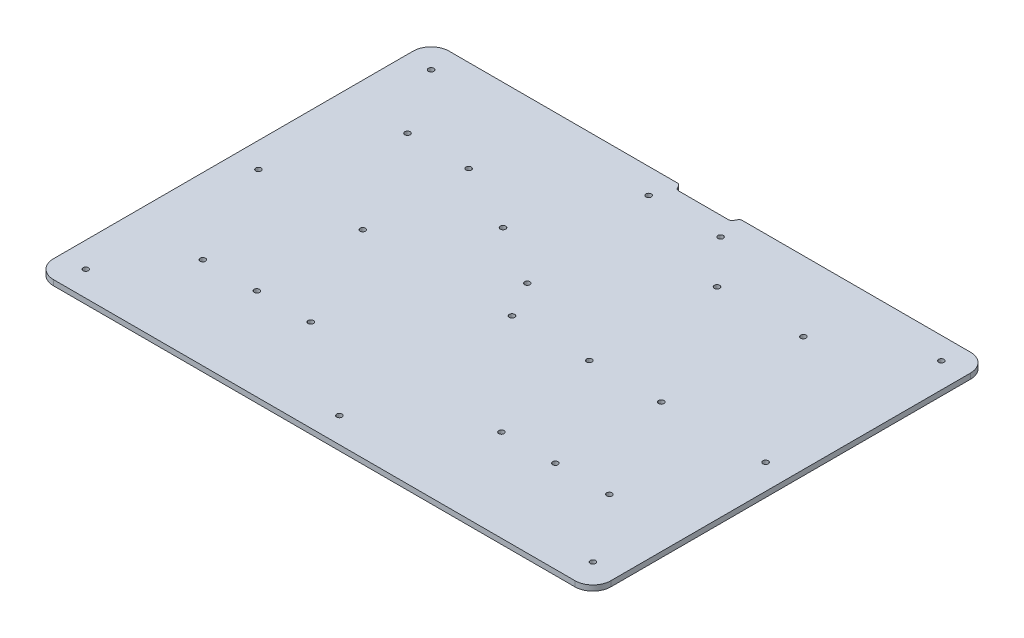
SolidWorks part; units mm, degrees
ref_plane "前视基准面" through (0, 0, 0) normal (0, 0, 1) x (1, 0, 0)
ref_plane "上视基准面" through (0, 0, 0) normal (0, 1, 0) x (1, 0, 0)
ref_plane "右视基准面" through (0, 0, 0) normal (1, 0, 0) x (0, 0, -1)
sketch "草图1" plane through (0, 0, 0) normal (0, 1, 0) x (1, 0, 0)
  line L0 (183.25, -128.5) -> (183.25, -131.5) construction
  line L1 (10, 0) -> (136.8844, 0)
  line L2 (0, -10) -> (0, -210)
  line L3 (10, -220) -> (300, -220)
  line L4 (310, -10) -> (310, -210)
  line L5 (28.75, -14.75) -> (47.25, -14.75) construction
  line L6 (28.75, -14.75) -> (28.75, -33.25) construction
  line L7 (28.75, -33.25) -> (47.25, -33.25) construction
  line L8 (173, -85) -> (173, 0) construction
  line L9 (173, -85) -> (310, -85) construction
  line L10 (190, -66) -> (190, 0) construction
  line L11 (215, -58) -> (215, 0) construction
  line L12 (241, -58) -> (241, 0) construction
  line L13 (247, -84) -> (247, 0) construction
  line L14 (222, -84) -> (222, 0) construction
  line L15 (0, -220) -> (310, 0) construction
  line L16 (241, -58) -> (310, -58) construction
  line L17 (247, -84) -> (310, -84) construction
  line L18 (215, -58) -> (310, -58) construction
  line L19 (222, -84) -> (310, -84) construction
  line L20 (190, -66) -> (310, -66) construction
  line L21 (310, -220) -> (0, 0) construction
  line L22 (141.1791, -3.5) -> (143.5, -3.5)
  line L23 (139.4291, -2.4682) -> (138.6344, -1.0318)
  line L24 (170.5709, -2.4682) -> (171.3656, -1.0318)
  line L25 (173.1156, 0) -> (300, 0)
  line L26 (155, -110) -> (155, -220) construction
  line L27 (47.25, -14.75) -> (47.25, -33.25) construction
  line L28 (28.75, -14.75) -> (47.25, -33.25) construction
  line L29 (28.75, -33.25) -> (47.25, -14.75) construction
  line L30 (52.75, -14.75) -> (71.25, -14.75) construction
  line L31 (52.75, -14.75) -> (52.75, -33.25) construction
  line L32 (52.75, -33.25) -> (71.25, -33.25) construction
  line L33 (71.25, -14.75) -> (71.25, -33.25) construction
  line L34 (52.75, -14.75) -> (71.25, -33.25) construction
  line L35 (52.75, -33.25) -> (71.25, -14.75) construction
  line L36 (76.75, -14.75) -> (95.25, -14.75) construction
  line L37 (76.75, -14.75) -> (76.75, -33.25) construction
  line L38 (76.75, -33.25) -> (95.25, -33.25) construction
  line L39 (95.25, -14.75) -> (95.25, -33.25) construction
  line L40 (76.75, -14.75) -> (95.25, -33.25) construction
  line L41 (76.75, -33.25) -> (95.25, -14.75) construction
  line L42 (100.75, -14.75) -> (119.25, -14.75) construction
  line L43 (100.75, -14.75) -> (100.75, -33.25) construction
  line L44 (100.75, -33.25) -> (119.25, -33.25) construction
  line L45 (119.25, -14.75) -> (119.25, -33.25) construction
  line L46 (100.75, -14.75) -> (119.25, -33.25) construction
  line L47 (100.75, -33.25) -> (119.25, -14.75) construction
  line L48 (188.75, -14.75) -> (207.25, -14.75) construction
  line L49 (188.75, -14.75) -> (188.75, -33.25) construction
  line L50 (188.75, -33.25) -> (207.25, -33.25) construction
  line L51 (207.25, -14.75) -> (207.25, -33.25) construction
  line L52 (188.75, -14.75) -> (207.25, -33.25) construction
  line L53 (188.75, -33.25) -> (207.25, -14.75) construction
  line L54 (212.75, -14.75) -> (231.25, -14.75) construction
  line L55 (212.75, -14.75) -> (212.75, -33.25) construction
  line L56 (212.75, -33.25) -> (231.25, -33.25) construction
  line L57 (231.25, -14.75) -> (231.25, -33.25) construction
  line L58 (212.75, -14.75) -> (231.25, -33.25) construction
  line L59 (212.75, -33.25) -> (231.25, -14.75) construction
  line L60 (236.75, -14.75) -> (255.25, -14.75) construction
  line L61 (236.75, -14.75) -> (236.75, -33.25) construction
  line L62 (236.75, -33.25) -> (255.25, -33.25) construction
  line L63 (255.25, -14.75) -> (255.25, -33.25) construction
  line L64 (236.75, -14.75) -> (255.25, -33.25) construction
  line L65 (236.75, -33.25) -> (255.25, -14.75) construction
  line L66 (260.75, -14.75) -> (279.25, -14.75) construction
  line L67 (260.75, -14.75) -> (260.75, -33.25) construction
  line L68 (260.75, -33.25) -> (279.25, -33.25) construction
  line L69 (279.25, -14.75) -> (279.25, -33.25) construction
  line L70 (260.75, -14.75) -> (279.25, -33.25) construction
  line L71 (260.75, -33.25) -> (279.25, -14.75) construction
  line L72 (183, -123) -> (197, -123) construction
  line L73 (183, -123) -> (183, -128.25) construction
  line L74 (183, -137) -> (197, -137) construction
  line L75 (197, -123) -> (197, -128.25) construction
  line L76 (183, -123) -> (197, -137) construction
  line L77 (183, -137) -> (197, -123) construction
  line L78 (183.25, -128.5) -> (183, -128.25) construction
  line L79 (183.25, -131.5) -> (183, -131.75) construction
  line L80 (196.75, -128.5) -> (196.75, -131.5) construction
  line L81 (196.75, -128.5) -> (197, -128.25) construction
  line L82 (196.75, -131.5) -> (197, -131.75) construction
  line L83 (183, -131.75) -> (183, -137) construction
  line L84 (197, -131.75) -> (197, -137) construction
  line L85 (31.25, -22.5) -> (31.25, -25.5) construction
  line L86 (31, -17) -> (45, -17) construction
  line L87 (31, -17) -> (31, -22.25) construction
  line L88 (31, -31) -> (45, -31) construction
  line L89 (45, -17) -> (45, -22.25) construction
  line L90 (31, -17) -> (45, -31) construction
  line L91 (31, -31) -> (45, -17) construction
  line L92 (31.25, -22.5) -> (31, -22.25) construction
  line L93 (31.25, -25.5) -> (31, -25.75) construction
  line L94 (44.75, -22.5) -> (44.75, -25.5) construction
  line L95 (44.75, -22.5) -> (45, -22.25) construction
  line L96 (44.75, -25.5) -> (45, -25.75) construction
  line L97 (31, -25.75) -> (31, -31) construction
  line L98 (45, -25.75) -> (45, -31) construction
  line L99 (55.25, -22.5) -> (55.25, -25.5) construction
  line L100 (55, -17) -> (69, -17) construction
  line L101 (55, -17) -> (55, -22.25) construction
  line L102 (55, -31) -> (69, -31) construction
  line L103 (69, -17) -> (69, -22.25) construction
  line L104 (55, -17) -> (69, -31) construction
  line L105 (55, -31) -> (69, -17) construction
  line L106 (55.25, -22.5) -> (55, -22.25) construction
  line L107 (55.25, -25.5) -> (55, -25.75) construction
  line L108 (68.75, -22.5) -> (68.75, -25.5) construction
  line L109 (68.75, -22.5) -> (69, -22.25) construction
  line L110 (68.75, -25.5) -> (69, -25.75) construction
  line L111 (55, -25.75) -> (55, -31) construction
  line L112 (69, -25.75) -> (69, -31) construction
  line L113 (79.25, -22.5) -> (79.25, -25.5) construction
  line L114 (79, -17) -> (93, -17) construction
  line L115 (79, -17) -> (79, -22.25) construction
  line L116 (79, -31) -> (93, -31) construction
  line L117 (93, -17) -> (93, -22.25) construction
  line L118 (79, -17) -> (93, -31) construction
  line L119 (79, -31) -> (93, -17) construction
  line L120 (79.25, -22.5) -> (79, -22.25) construction
  line L121 (79.25, -25.5) -> (79, -25.75) construction
  line L122 (92.75, -22.5) -> (92.75, -25.5) construction
  line L123 (92.75, -22.5) -> (93, -22.25) construction
  line L124 (92.75, -25.5) -> (93, -25.75) construction
  line L125 (79, -25.75) -> (79, -31) construction
  line L126 (93, -25.75) -> (93, -31) construction
  line L127 (103.25, -22.5) -> (103.25, -25.5) construction
  line L128 (103, -17) -> (117, -17) construction
  line L129 (103, -17) -> (103, -22.25) construction
  line L130 (103, -31) -> (117, -31) construction
  line L131 (117, -17) -> (117, -22.25) construction
  line L132 (103, -17) -> (117, -31) construction
  line L133 (103, -31) -> (117, -17) construction
  line L134 (103.25, -22.5) -> (103, -22.25) construction
  line L135 (103.25, -25.5) -> (103, -25.75) construction
  line L136 (116.75, -22.5) -> (116.75, -25.5) construction
  line L137 (116.75, -22.5) -> (117, -22.25) construction
  line L138 (116.75, -25.5) -> (117, -25.75) construction
  line L139 (103, -25.75) -> (103, -31) construction
  line L140 (117, -25.75) -> (117, -31) construction
  line L141 (191.25, -22.5) -> (191.25, -25.5) construction
  line L142 (191, -17) -> (205, -17) construction
  line L143 (191, -17) -> (191, -22.25) construction
  line L144 (191, -31) -> (205, -31) construction
  line L145 (205, -17) -> (205, -22.25) construction
  line L146 (191, -17) -> (205, -31) construction
  line L147 (191, -31) -> (205, -17) construction
  line L148 (191.25, -22.5) -> (191, -22.25) construction
  line L149 (191.25, -25.5) -> (191, -25.75) construction
  line L150 (204.75, -22.5) -> (204.75, -25.5) construction
  line L151 (204.75, -22.5) -> (205, -22.25) construction
  line L152 (204.75, -25.5) -> (205, -25.75) construction
  line L153 (191, -25.75) -> (191, -31) construction
  line L154 (205, -25.75) -> (205, -31) construction
  line L155 (215.25, -22.5) -> (215.25, -25.5) construction
  line L156 (215, -17) -> (229, -17) construction
  line L157 (215, -17) -> (215, -22.25) construction
  line L158 (215, -31) -> (229, -31) construction
  line L159 (229, -17) -> (229, -22.25) construction
  line L160 (215, -17) -> (229, -31) construction
  line L161 (215, -31) -> (229, -17) construction
  line L162 (215.25, -22.5) -> (215, -22.25) construction
  line L163 (215.25, -25.5) -> (215, -25.75) construction
  line L164 (228.75, -22.5) -> (228.75, -25.5) construction
  line L165 (228.75, -22.5) -> (229, -22.25) construction
  line L166 (228.75, -25.5) -> (229, -25.75) construction
  line L167 (215, -25.75) -> (215, -31) construction
  line L168 (229, -25.75) -> (229, -31) construction
  line L169 (239.25, -22.5) -> (239.25, -25.5) construction
  line L170 (239, -17) -> (253, -17) construction
  line L171 (239, -17) -> (239, -22.25) construction
  line L172 (239, -31) -> (253, -31) construction
  line L173 (253, -17) -> (253, -22.25) construction
  line L174 (239, -17) -> (253, -31) construction
  line L175 (239, -31) -> (253, -17) construction
  line L176 (239.25, -22.5) -> (239, -22.25) construction
  line L177 (239.25, -25.5) -> (239, -25.75) construction
  line L178 (252.75, -22.5) -> (252.75, -25.5) construction
  line L179 (252.75, -22.5) -> (253, -22.25) construction
  line L180 (252.75, -25.5) -> (253, -25.75) construction
  line L181 (239, -25.75) -> (239, -31) construction
  line L182 (253, -25.75) -> (253, -31) construction
  line L183 (263.25, -22.5) -> (263.25, -25.5) construction
  line L184 (263, -17) -> (277, -17) construction
  line L185 (263, -17) -> (263, -22.25) construction
  line L186 (263, -31) -> (277, -31) construction
  line L187 (277, -17) -> (277, -22.25) construction
  line L188 (263, -17) -> (277, -31) construction
  line L189 (263, -31) -> (277, -17) construction
  line L190 (263.25, -22.5) -> (263, -22.25) construction
  line L191 (263.25, -25.5) -> (263, -25.75) construction
  line L192 (276.75, -22.5) -> (276.75, -25.5) construction
  line L193 (276.75, -22.5) -> (277, -22.25) construction
  line L194 (276.75, -25.5) -> (277, -25.75) construction
  line L195 (263, -25.75) -> (263, -31) construction
  line L196 (277, -25.75) -> (277, -31) construction
  line L197 (259.25, -64.5) -> (259.25, -67.5) construction
  line L198 (259, -59) -> (273, -59) construction
  line L199 (259, -59) -> (259, -64.25) construction
  line L200 (259, -73) -> (273, -73) construction
  line L201 (273, -59) -> (273, -64.25) construction
  line L202 (259, -59) -> (273, -73) construction
  line L203 (259, -73) -> (273, -59) construction
  line L204 (259.25, -64.5) -> (259, -64.25) construction
  line L205 (259.25, -67.5) -> (259, -67.75) construction
  line L206 (272.75, -64.5) -> (272.75, -67.5) construction
  line L207 (272.75, -64.5) -> (273, -64.25) construction
  line L208 (272.75, -67.5) -> (273, -67.75) construction
  line L209 (259, -67.75) -> (259, -73) construction
  line L210 (273, -67.75) -> (273, -73) construction
  line L211 (240.25, -82.5) -> (240.25, -85.5) construction
  line L212 (240, -77) -> (254, -77) construction
  line L213 (240, -77) -> (240, -82.25) construction
  line L214 (240, -91) -> (254, -91) construction
  line L215 (254, -77) -> (254, -82.25) construction
  line L216 (240, -77) -> (254, -91) construction
  line L217 (240, -91) -> (254, -77) construction
  line L218 (240.25, -82.5) -> (240, -82.25) construction
  line L219 (240.25, -85.5) -> (240, -85.75) construction
  line L220 (253.75, -82.5) -> (253.75, -85.5) construction
  line L221 (253.75, -82.5) -> (254, -82.25) construction
  line L222 (253.75, -85.5) -> (254, -85.75) construction
  line L223 (240, -85.75) -> (240, -91) construction
  line L224 (254, -85.75) -> (254, -91) construction
  line L225 (234.25, -56.5) -> (234.25, -59.5) construction
  line L226 (234, -51) -> (248, -51) construction
  line L227 (234, -51) -> (234, -56.25) construction
  line L228 (234, -65) -> (248, -65) construction
  line L229 (248, -51) -> (248, -56.25) construction
  line L230 (234, -51) -> (248, -65) construction
  line L231 (234, -65) -> (248, -51) construction
  line L232 (234.25, -56.5) -> (234, -56.25) construction
  line L233 (234.25, -59.5) -> (234, -59.75) construction
  line L234 (247.75, -56.5) -> (247.75, -59.5) construction
  line L235 (247.75, -56.5) -> (248, -56.25) construction
  line L236 (247.75, -59.5) -> (248, -59.75) construction
  line L237 (234, -59.75) -> (234, -65) construction
  line L238 (248, -59.75) -> (248, -65) construction
  line L239 (215.25, -82.5) -> (215.25, -85.5) construction
  line L240 (215, -77) -> (229, -77) construction
  line L241 (215, -77) -> (215, -82.25) construction
  line L242 (215, -91) -> (229, -91) construction
  line L243 (229, -77) -> (229, -82.25) construction
  line L244 (215, -77) -> (229, -91) construction
  line L245 (215, -91) -> (229, -77) construction
  line L246 (215.25, -82.5) -> (215, -82.25) construction
  line L247 (215.25, -85.5) -> (215, -85.75) construction
  line L248 (228.75, -82.5) -> (228.75, -85.5) construction
  line L249 (228.75, -82.5) -> (229, -82.25) construction
  line L250 (228.75, -85.5) -> (229, -85.75) construction
  line L251 (215, -85.75) -> (215, -91) construction
  line L252 (229, -85.75) -> (229, -91) construction
  line L253 (29.25, -95.5) -> (29.25, -98.5) construction
  line L254 (29, -90) -> (43, -90) construction
  line L255 (29, -90) -> (29, -95.25) construction
  line L256 (29, -104) -> (43, -104) construction
  line L257 (43, -90) -> (43, -95.25) construction
  line L258 (29, -90) -> (43, -104) construction
  line L259 (29, -104) -> (43, -90) construction
  line L260 (29.25, -95.5) -> (29, -95.25) construction
  line L261 (29.25, -98.5) -> (29, -98.75) construction
  line L262 (42.75, -95.5) -> (42.75, -98.5) construction
  line L263 (42.75, -95.5) -> (43, -95.25) construction
  line L264 (42.75, -98.5) -> (43, -98.75) construction
  line L265 (29, -98.75) -> (29, -104) construction
  line L266 (43, -98.75) -> (43, -104) construction
  line L267 (51.25, -78.5) -> (51.25, -81.5) construction
  line L268 (51, -73) -> (65, -73) construction
  line L269 (51, -73) -> (51, -78.25) construction
  line L270 (51, -87) -> (65, -87) construction
  line L271 (65, -73) -> (65, -78.25) construction
  line L272 (51, -73) -> (65, -87) construction
  line L273 (51, -87) -> (65, -73) construction
  line L274 (51.25, -78.5) -> (51, -78.25) construction
  line L275 (51.25, -81.5) -> (51, -81.75) construction
  line L276 (64.75, -78.5) -> (64.75, -81.5) construction
  line L277 (64.75, -78.5) -> (65, -78.25) construction
  line L278 (64.75, -81.5) -> (65, -81.75) construction
  line L279 (51, -81.75) -> (51, -87) construction
  line L280 (65, -81.75) -> (65, -87) construction
  line L281 (77.25, -75.5) -> (77.25, -78.5) construction
  line L282 (77, -70) -> (91, -70) construction
  line L283 (77, -70) -> (77, -75.25) construction
  line L284 (77, -84) -> (91, -84) construction
  line L285 (91, -70) -> (91, -75.25) construction
  line L286 (77, -70) -> (91, -84) construction
  line L287 (77, -84) -> (91, -70) construction
  line L288 (77.25, -75.5) -> (77, -75.25) construction
  line L289 (77.25, -78.5) -> (77, -78.75) construction
  line L290 (90.75, -75.5) -> (90.75, -78.5) construction
  line L291 (90.75, -75.5) -> (91, -75.25) construction
  line L292 (90.75, -78.5) -> (91, -78.75) construction
  line L293 (77, -78.75) -> (77, -84) construction
  line L294 (91, -78.75) -> (91, -84) construction
  line L295 (82.25, -51.5) -> (82.25, -54.5) construction
  line L296 (82, -46) -> (96, -46) construction
  line L297 (82, -46) -> (82, -51.25) construction
  line L298 (82, -60) -> (96, -60) construction
  line L299 (96, -46) -> (96, -51.25) construction
  line L300 (82, -46) -> (96, -60) construction
  line L301 (82, -60) -> (96, -46) construction
  line L302 (82.25, -51.5) -> (82, -51.25) construction
  line L303 (82.25, -54.5) -> (82, -54.75) construction
  line L304 (95.75, -51.5) -> (95.75, -54.5) construction
  line L305 (95.75, -51.5) -> (96, -51.25) construction
  line L306 (95.75, -54.5) -> (96, -54.75) construction
  line L307 (82, -54.75) -> (82, -60) construction
  line L308 (96, -54.75) -> (96, -60) construction
  line L309 (99.25, -88.5) -> (99.25, -91.5) construction
  line L310 (99, -83) -> (113, -83) construction
  line L311 (99, -83) -> (99, -88.25) construction
  line L312 (99, -97) -> (113, -97) construction
  line L313 (113, -83) -> (113, -88.25) construction
  line L314 (99, -83) -> (113, -97) construction
  line L315 (99, -97) -> (113, -83) construction
  line L316 (99.25, -88.5) -> (99, -88.25) construction
  line L317 (99.25, -91.5) -> (99, -91.75) construction
  line L318 (112.75, -88.5) -> (112.75, -91.5) construction
  line L319 (112.75, -88.5) -> (113, -88.25) construction
  line L320 (112.75, -91.5) -> (113, -91.75) construction
  line L321 (99, -91.75) -> (99, -97) construction
  line L322 (113, -91.75) -> (113, -97) construction
  line L323 (208.25, -56.5) -> (208.25, -59.5) construction
  line L324 (208, -51) -> (222, -51) construction
  line L325 (208, -51) -> (208, -56.25) construction
  line L326 (208, -65) -> (222, -65) construction
  line L327 (222, -51) -> (222, -56.25) construction
  line L328 (208, -51) -> (222, -65) construction
  line L329 (208, -65) -> (222, -51) construction
  line L330 (208.25, -56.5) -> (208, -56.25) construction
  line L331 (208.25, -59.5) -> (208, -59.75) construction
  line L332 (221.75, -56.5) -> (221.75, -59.5) construction
  line L333 (221.75, -56.5) -> (222, -56.25) construction
  line L334 (221.75, -59.5) -> (222, -59.75) construction
  line L335 (208, -59.75) -> (208, -65) construction
  line L336 (222, -59.75) -> (222, -65) construction
  line L337 (183.25, -64.5) -> (183.25, -67.5) construction
  line L338 (183, -59) -> (197, -59) construction
  line L339 (183, -59) -> (183, -64.25) construction
  line L340 (183, -73) -> (197, -73) construction
  line L341 (197, -59) -> (197, -64.25) construction
  line L342 (183, -59) -> (197, -73) construction
  line L343 (183, -73) -> (197, -59) construction
  line L344 (183.25, -64.5) -> (183, -64.25) construction
  line L345 (183.25, -67.5) -> (183, -67.75) construction
  line L346 (196.75, -64.5) -> (196.75, -67.5) construction
  line L347 (196.75, -64.5) -> (197, -64.25) construction
  line L348 (196.75, -67.5) -> (197, -67.75) construction
  line L349 (183, -67.75) -> (183, -73) construction
  line L350 (197, -67.75) -> (197, -73) construction
  line L351 (191.25, -88.5) -> (191.25, -91.5) construction
  line L352 (191, -83) -> (205, -83) construction
  line L353 (191, -83) -> (191, -88.25) construction
  line L354 (191, -97) -> (205, -97) construction
  line L355 (205, -83) -> (205, -88.25) construction
  line L356 (191, -83) -> (205, -97) construction
  line L357 (191, -97) -> (205, -83) construction
  line L358 (191.25, -88.5) -> (191, -88.25) construction
  line L359 (191.25, -91.5) -> (191, -91.75) construction
  line L360 (204.75, -88.5) -> (204.75, -91.5) construction
  line L361 (204.75, -88.5) -> (205, -88.25) construction
  line L362 (204.75, -91.5) -> (205, -91.75) construction
  line L363 (191, -91.75) -> (191, -97) construction
  line L364 (205, -91.75) -> (205, -97) construction
  line L365 (166.25, -83.5) -> (166.25, -86.5) construction
  line L366 (166, -78) -> (180, -78) construction
  line L367 (166, -78) -> (166, -83.25) construction
  line L368 (166, -92) -> (180, -92) construction
  line L369 (180, -78) -> (180, -83.25) construction
  line L370 (166, -78) -> (180, -92) construction
  line L371 (166, -92) -> (180, -78) construction
  line L372 (166.25, -83.5) -> (166, -83.25) construction
  line L373 (166.25, -86.5) -> (166, -86.75) construction
  line L374 (179.75, -83.5) -> (179.75, -86.5) construction
  line L375 (179.75, -83.5) -> (180, -83.25) construction
  line L376 (179.75, -86.5) -> (180, -86.75) construction
  line L377 (166, -86.75) -> (166, -92) construction
  line L378 (180, -86.75) -> (180, -92) construction
  line L379 (107.25, -128.5) -> (107.25, -131.5) construction
  line L380 (107, -123) -> (121, -123) construction
  line L381 (107, -123) -> (107, -128.25) construction
  line L382 (107, -137) -> (121, -137) construction
  line L383 (121, -123) -> (121, -128.25) construction
  line L384 (107, -123) -> (121, -137) construction
  line L385 (107, -137) -> (121, -123) construction
  line L386 (107.25, -128.5) -> (107, -128.25) construction
  line L387 (107.25, -131.5) -> (107, -131.75) construction
  line L388 (120.75, -128.5) -> (120.75, -131.5) construction
  line L389 (120.75, -128.5) -> (121, -128.25) construction
  line L390 (120.75, -131.5) -> (121, -131.75) construction
  line L391 (107, -131.75) -> (107, -137) construction
  line L392 (121, -131.75) -> (121, -137) construction
  line L393 (138.25, -136.5) -> (138.25, -139.5) construction
  line L394 (138, -131) -> (152, -131) construction
  line L395 (138, -131) -> (138, -136.25) construction
  line L396 (138, -145) -> (152, -145) construction
  line L397 (152, -131) -> (152, -136.25) construction
  line L398 (138, -131) -> (152, -145) construction
  line L399 (138, -145) -> (152, -131) construction
  line L400 (138.25, -136.5) -> (138, -136.25) construction
  line L401 (138.25, -139.5) -> (138, -139.75) construction
  line L402 (151.75, -136.5) -> (151.75, -139.5) construction
  line L403 (151.75, -136.5) -> (152, -136.25) construction
  line L404 (151.75, -139.5) -> (152, -139.75) construction
  line L405 (138, -139.75) -> (138, -145) construction
  line L406 (152, -139.75) -> (152, -145) construction
  line L407 (166.5, -3.5) -> (168.8209, -3.5)
  line L409 (143.5, -3.5) -> (143.5, -55.5) construction
  line L410 (143.5, -55.5) -> (166.5, -55.5) construction
  line L411 (166.5, -3.5) -> (166.5, -55.5) construction
  line L412 (143.5, -3.5) -> (166.5, -55.5) construction
  line L413 (143.5, -55.5) -> (166.5, -3.5) construction
  line L414 (143.5, -3.5) -> (166.5, -3.5)
  arc A0 (10, 0) -> (0, -10) centre (10, -10) ccw
  arc A1 (0, -210) -> (10, -220) centre (10, -210) ccw
  arc A2 (300, -220) -> (310, -210) centre (300, -210) ccw
  arc A3 (300, 0) -> (310, -10) centre (300, -10) cw
  circle A8 centre (173, -85) radius 11 construction
  circle A9 centre (190, -66) radius 11 construction
  circle A11 centre (215, -58) radius 11 construction
  circle A12 centre (222, -84) radius 11 construction
  circle A13 centre (247, -84) radius 11 construction
  circle A14 centre (241, -58) radius 11 construction
  circle A15 centre (14, -14) radius 1.5
  circle A16 centre (14, -206) radius 1.5
  circle A17 centre (296, -206) radius 1.5
  circle A18 centre (296, -12.2857) radius 1.5
  arc A19 (173.1156, 0) -> (171.3656, -1.0318) centre (173.1156, -2) ccw
  arc A20 (170.5709, -2.4682) -> (168.8209, -3.5) centre (168.8209, -1.5) cw
  arc A21 (141.1791, -3.5) -> (139.4291, -2.4682) centre (141.1791, -1.5) cw
  arc A22 (136.8844, 0) -> (138.6344, -1.0318) centre (136.8844, -2) cw
  circle A24 centre (198, -90) radius 11 construction
  circle A25 centre (114, -130) radius 13.5 construction
  circle A26 centre (190, -130) radius 13.5 construction
  circle A27 centre (155, -206) radius 1.5
  circle A28 centre (175, -14) radius 1.5
  circle A29 centre (145, -138) radius 11 construction
  circle A30 centre (106, -90) radius 11 construction
  circle A31 centre (84, -77) radius 11 construction
  circle A32 centre (58, -80) radius 11 construction
  circle A33 centre (36, -97) radius 11 construction
  circle A34 centre (89, -53) radius 11 construction
  circle A35 centre (266, -66) radius 11 construction
  circle A36 centre (110, -24) radius 4.5 construction
  circle A37 centre (86, -24) radius 4.5 construction
  circle A38 centre (62, -24) radius 4.5 construction
  circle A39 centre (38, -24) radius 4.5 construction
  circle A40 centre (198, -24) radius 4.5 construction
  circle A41 centre (222, -24) radius 4.5 construction
  circle A42 centre (246, -24) radius 4.5 construction
  circle A43 centre (270, -24) radius 4.5 construction
  circle A48 centre (135, -14) radius 1.5
  circle A51 centre (296, -110) radius 1.5
  circle A52 centre (14, -110) radius 1.5
  circle A53 centre (155, -110) radius 1.5
  circle A54 centre (72, -110) radius 1.5
  circle A55 centre (72, -168.9032) radius 1.5
  circle A56 centre (72, -51.0968) radius 1.5
  circle A57 centre (42, -168.9032) radius 1.5
  circle A58 centre (102, -168.9032) radius 1.5
  circle A59 centre (238, -110) radius 1.5
  circle A60 centre (238, -168.9032) radius 1.5
  circle A61 centre (268, -168.9032) radius 1.5
  circle A62 centre (208, -168.9032) radius 1.5
  circle A63 centre (246, -39) radius 1.5
  circle A64 centre (198, -39) radius 1.5
  circle A65 centre (110, -70) radius 1.5
  circle A66 centre (38, -51.0968) radius 1.5
  circle A67 centre (198, -110) radius 1.5
  circle A68 centre (143.5, -90) radius 1.5
  point P8 (0, 0)
  point P12 (0, -220)
  point P15 (310, -220)
  point P18 (310, 0)
  point P70 (171.9365, 0)
  point P73 (170, -3.5)
  point P76 (140, -3.5)
  point P79 (138.0635, 0)
  point P147 (190, -130)
  point P152 (155, -29.5)
  point P155 (183.25, -130)
  point P160 (196.75, -130)
  point P163 (38, -24)
  point P170 (31.25, -24)
  point P175 (44.75, -24)
  point P180 (62, -24)
  point P187 (55.25, -24)
  point P192 (68.75, -24)
  point P196 (86, -24)
  point P203 (79.25, -24)
  point P208 (92.75, -24)
  point P213 (110, -24)
  point P220 (103.25, -24)
  point P225 (116.75, -24)
  point P229 (198, -24)
  point P236 (191.25, -24)
  point P241 (204.75, -24)
  point P245 (222, -24)
  point P252 (215.25, -24)
  point P257 (228.75, -24)
  point P261 (246, -24)
  point P268 (239.25, -24)
  point P273 (252.75, -24)
  point P277 (270, -24)
  point P284 (263.25, -24)
  point P289 (276.75, -24)
  point P293 (266, -66)
  point P300 (259.25, -66)
  point P305 (272.75, -66)
  point P310 (247, -84)
  point P317 (240.25, -84)
  point P322 (253.75, -84)
  point P326 (241, -58)
  point P333 (234.25, -58)
  point P338 (247.75, -58)
  point P342 (222, -84)
  point P349 (215.25, -84)
  point P354 (228.75, -84)
  point P358 (36, -97)
  point P365 (29.25, -97)
  point P370 (42.75, -97)
  point P374 (58, -80)
  point P381 (51.25, -80)
  point P386 (64.75, -80)
  point P390 (84, -77)
  point P397 (77.25, -77)
  point P402 (90.75, -77)
  point P407 (89, -53)
  point P414 (82.25, -53)
  point P419 (95.75, -53)
  point P423 (106, -90)
  point P430 (99.25, -90)
  point P435 (112.75, -90)
  point P439 (215, -58)
  point P446 (208.25, -58)
  point P451 (221.75, -58)
  point P455 (190, -66)
  point P462 (183.25, -66)
  point P467 (196.75, -66)
  point P471 (198, -90)
  point P478 (191.25, -90)
  point P483 (204.75, -90)
  point P492 (173, -85)
  point P499 (166.25, -85)
  point P504 (179.75, -85)
  point P508 (114, -130)
  point P515 (107.25, -130)
  point P520 (120.75, -130)
  point P524 (145, -138)
  point P531 (138.25, -138)
  point P536 (151.75, -138)
  dimension "D3" = 10
  dimension "D7" = 90
  dimension "D10" = 22
  dimension "D15" = 53
  dimension "D16" = 22
  dimension "D19" = 22
  dimension "D20" = 22
  dimension "D21" = 22
  dimension "D22" = 84
  dimension "D23" = 22
  dimension "D24" = 22
  dimension "D32" = 22
  dimension "D34" = 3
  dimension "D37" = 3
  dimension "D40" = 3
  dimension "D43" = 3
  dimension "D47" = 3.5
  dimension "D50" = 140
  dimension "D51" = 2
  dimension "D52" = 90
  dimension "D54" = 27
  dimension "D56" = 27
  dimension "D59" = 3
  dimension "D61" = 14
  dimension "D62" = 3
  dimension "D64" = 22
  dimension "D8" = 22
  dimension "D9" = 22
  dimension "D11" = 22
  dimension "D12" = 22
  dimension "D13" = 22
  dimension "D76" = 9
  dimension "D84" = 9
  dimension "D86" = 3
  dimension "D89" = 18.5
  dimension "D92" = 18.5
  dimension "D95" = 18.5
  dimension "D98" = 3
  dimension "D101" = 18.5
  dimension "D103" = 18.5
  dimension "D87" = 3
  dimension "D301" = 3
  dimension "D302" = 3
  dimension "D304" = 3
  dimension "D305" = 3
  dimension "D306" = 3
  dimension "D308" = 3
  dimension "D310" = 3
  dimension "D312" = 3
  dimension "D313" = 3
  dimension "D314" = 3
  dimension "D317" = 3
  dimension "D319" = 3
  dimension "D321" = 3
  dimension "D323" = 3
  dimension "D324" = 3
  dimension "D325" = 3
  dimension "D1" = 220
  dimension "D2" = 310
  dimension "D14" = 89
  dimension "D17" = 85
  dimension "D18" = 137
  dimension "D25" = 66
  dimension "D26" = 120
  dimension "D27" = 36
  dimension "D28" = 58
  dimension "D29" = 95
  dimension "D30" = 88
  dimension "D31" = 69
  dimension "D33" = 63
  dimension "D35" = 14
  dimension "D36" = 14
  dimension "D38" = 14
  dimension "D39" = 14
  dimension "D41" = 14
  dimension "D42" = 14
  dimension "D44" = 14
  dimension "D45" = 12.2857
  dimension "D46" = 4
  dimension "D48" = 30
  dimension "D49" = 4
  dimension "D53" = 112
  dimension "D55" = 114
  dimension "D57" = 90
  dimension "D58" = 120
  dimension "D60" = 14
  dimension "D63" = 135
  dimension "D65" = 82
  dimension "D66" = 145
  dimension "D67" = 97
  dimension "D68" = 80
  dimension "D69" = 58
  dimension "D70" = 84
  dimension "D71" = 77
  dimension "D72" = 90
  dimension "D73" = 106
  dimension "D74" = 44
  dimension "D75" = 66
  dimension "D78" = 24
  dimension "D79" = 110
  dimension "D80" = 24
  dimension "D82" = 24
  dimension "D83" = 24
  dimension "D85" = 40
  dimension "D88" = 18.5
  dimension "D90" = 18.5
  dimension "D91" = 18.5
  dimension "D93" = 18.5
  dimension "D94" = 18.5
  dimension "D96" = 18.5
  dimension "D97" = 18.5
  dimension "D99" = 14
  dimension "D100" = 135
  dimension "D102" = 18.5
  dimension "D104" = 18.5
  dimension "D105" = 18.5
  dimension "D106" = 18.5
  dimension "D107" = 14
  dimension "D108" = 14
  dimension "D109" = 0.25
  dimension "D110" = 3
  dimension "D111" = 135
  dimension "D112" = 3
  dimension "D113" = 0.25
  dimension "D114" = 135
  dimension "D115" = 14
  dimension "D116" = 14
  dimension "D117" = 0.25
  dimension "D118" = 3
  dimension "D119" = 135
  dimension "D120" = 3
  dimension "D121" = 0.25
  dimension "D122" = 135
  dimension "D123" = 14
  dimension "D124" = 14
  dimension "D125" = 0.25
  dimension "D126" = 3
  dimension "D127" = 135
  dimension "D128" = 3
  dimension "D129" = 0.25
  dimension "D130" = 135
  dimension "D131" = 14
  dimension "D132" = 14
  dimension "D133" = 0.25
  dimension "D134" = 3
  dimension "D135" = 135
  dimension "D136" = 3
  dimension "D137" = 0.25
  dimension "D138" = 135
  dimension "D139" = 14
  dimension "D140" = 14
  dimension "D141" = 0.25
  dimension "D142" = 3
  dimension "D143" = 135
  dimension "D144" = 3
  dimension "D145" = 0.25
  dimension "D146" = 135
  dimension "D147" = 14
  dimension "D148" = 14
  dimension "D149" = 0.25
  dimension "D150" = 3
  dimension "D151" = 135
  dimension "D152" = 3
  dimension "D153" = 0.25
  dimension "D154" = 135
  dimension "D155" = 14
  dimension "D156" = 14
  dimension "D157" = 0.25
  dimension "D158" = 3
  dimension "D159" = 135
  dimension "D160" = 3
  dimension "D161" = 0.25
  dimension "D162" = 135
  dimension "D163" = 14
  dimension "D164" = 14
  dimension "D165" = 0.25
  dimension "D166" = 3
  dimension "D167" = 135
  dimension "D168" = 3
  dimension "D169" = 0.25
  dimension "D170" = 135
  dimension "D171" = 14
  dimension "D172" = 14
  dimension "D173" = 0.25
  dimension "D174" = 3
  dimension "D175" = 135
  dimension "D176" = 3
  dimension "D177" = 0.25
  dimension "D178" = 135
  dimension "D179" = 14
  dimension "D180" = 14
  dimension "D181" = 0.25
  dimension "D182" = 3
  dimension "D183" = 135
  dimension "D184" = 3
  dimension "D185" = 0.25
  dimension "D186" = 135
  dimension "D187" = 14
  dimension "D188" = 14
  dimension "D189" = 0.25
  dimension "D190" = 3
  dimension "D191" = 135
  dimension "D192" = 3
  dimension "D193" = 0.25
  dimension "D194" = 135
  dimension "D195" = 14
  dimension "D196" = 14
  dimension "D197" = 0.25
  dimension "D198" = 3
  dimension "D199" = 135
  dimension "D200" = 3
  dimension "D201" = 0.25
  dimension "D202" = 135
  dimension "D203" = 14
  dimension "D204" = 14
  dimension "D205" = 0.25
  dimension "D206" = 3
  dimension "D207" = 135
  dimension "D208" = 3
  dimension "D209" = 0.25
  dimension "D210" = 135
  dimension "D211" = 14
  dimension "D212" = 14
  dimension "D213" = 0.25
  dimension "D214" = 3
  dimension "D215" = 135
  dimension "D216" = 3
  dimension "D217" = 0.25
  dimension "D218" = 135
  dimension "D219" = 14
  dimension "D220" = 14
  dimension "D221" = 0.25
  dimension "D222" = 3
  dimension "D223" = 135
  dimension "D224" = 3
  dimension "D225" = 0.25
  dimension "D226" = 135
  dimension "D227" = 14
  dimension "D228" = 14
  dimension "D229" = 0.25
  dimension "D230" = 3
  dimension "D231" = 135
  dimension "D232" = 3
  dimension "D233" = 0.25
  dimension "D234" = 135
  dimension "D235" = 14
  dimension "D236" = 14
  dimension "D237" = 0.25
  dimension "D238" = 3
  dimension "D239" = 135
  dimension "D240" = 3
  dimension "D241" = 0.25
  dimension "D242" = 135
  dimension "D243" = 14
  dimension "D244" = 14
  dimension "D245" = 0.25
  dimension "D246" = 3
  dimension "D247" = 135
  dimension "D248" = 3
  dimension "D249" = 0.25
  dimension "D250" = 135
  dimension "D251" = 14
  dimension "D252" = 14
  dimension "D253" = 0.25
  dimension "D254" = 3
  dimension "D255" = 135
  dimension "D256" = 3
  dimension "D257" = 0.25
  dimension "D258" = 135
  dimension "D259" = 14
  dimension "D260" = 14
  dimension "D261" = 0.25
  dimension "D262" = 3
  dimension "D263" = 135
  dimension "D264" = 3
  dimension "D265" = 0.25
  dimension "D266" = 135
  dimension "D267" = 14
  dimension "D268" = 14
  dimension "D269" = 0.25
  dimension "D270" = 3
  dimension "D271" = 135
  dimension "D272" = 3
  dimension "D273" = 0.25
  dimension "D274" = 135
  dimension "D275" = 14
  dimension "D276" = 14
  dimension "D277" = 0.25
  dimension "D278" = 3
  dimension "D279" = 135
  dimension "D280" = 3
  dimension "D281" = 0.25
  dimension "D282" = 135
  dimension "D283" = 14
  dimension "D284" = 14
  dimension "D285" = 0.25
  dimension "D286" = 3
  dimension "D287" = 135
  dimension "D288" = 3
  dimension "D289" = 0.25
  dimension "D290" = 135
  dimension "D291" = 14
  dimension "D292" = 14
  dimension "D293" = 0.25
  dimension "D294" = 3
  dimension "D295" = 135
  dimension "D296" = 3
  dimension "D297" = 0.25
  dimension "D298" = 135
  dimension "D299" = 23
  dimension "D300" = 52
  dimension "D303" = 72
  dimension "D307" = 30
  dimension "D309" = 30
  dimension "D311" = 72
  dimension "D315" = 30
  dimension "D316" = 30
  dimension "D318" = 15
  dimension "D320" = 15
  dimension "D322" = 46
  dimension "D77" = 4
  dimension "D81" = 4
extrude "凸台-拉伸1" add sketch "草图1" along normal blind 3
